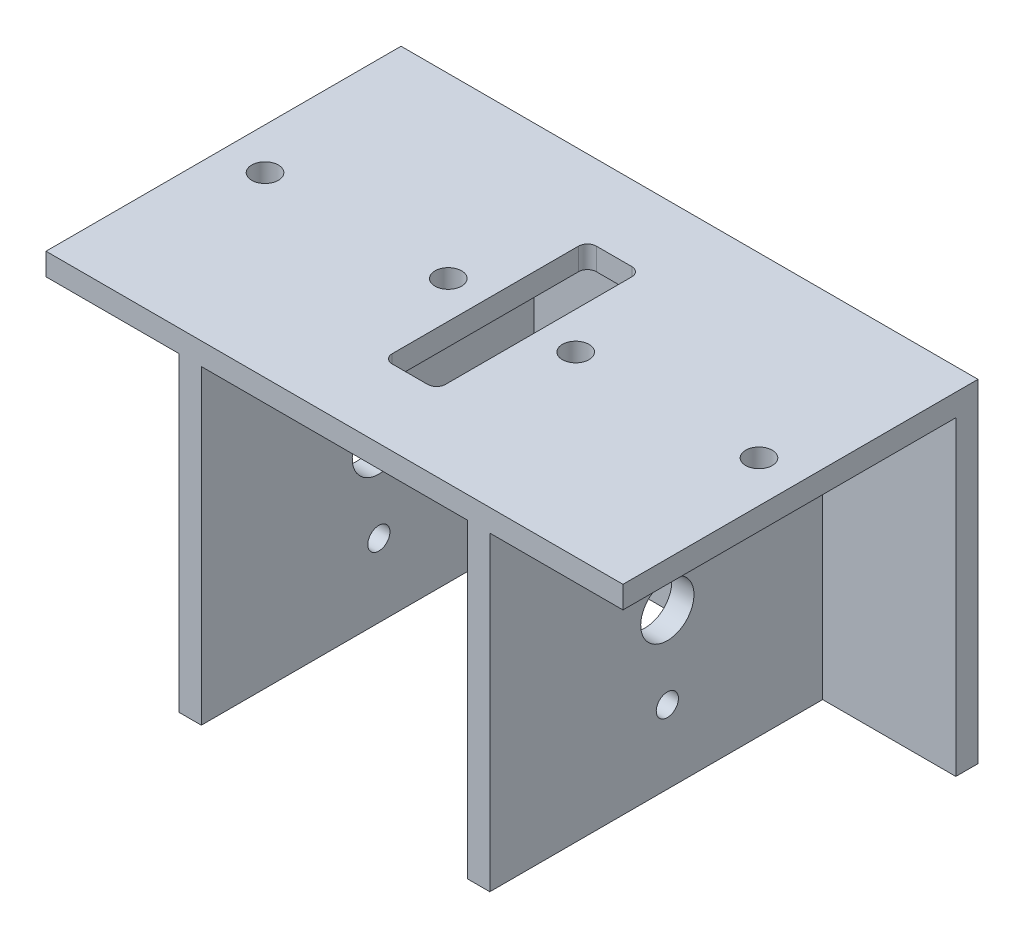
SolidWorks part; units mm, degrees
ref_plane "Front Plane" through (0, 0, 0) normal (0, 0, 1) x (1, 0, 0)
ref_plane "Top Plane" through (0, 0, 0) normal (0, 1, 0) x (1, 0, 0)
ref_plane "Right Plane" through (0, 0, 0) normal (1, 0, 0) x (0, 0, -1)
sketch "Sketch1" plane through (0, 0, 0) normal (0, 1, 0) x (1, 0, 0)
  line L0 (0, 18.2197) -> (0, -18.3609) construction
  line L1 (-19.3496, 0) -> (20.197, 0) construction
  line L2 (-35, 0) -> (-35, -10) construction
  line L3 (65, 40) -> (-65, 40)
  line L4 (-65, 40) -> (-65, -40)
  line L5 (65, -40) -> (-65, -40)
  line L6 (65, 40) -> (65, -40)
  line L7 (6, 23) -> (-6, 23)
  line L8 (-6, 23) -> (-6, -23)
  line L9 (6, -23) -> (-6, -23)
  line L10 (6, 23) -> (6, -23)
  circle A0 centre (-35, 0) radius 10 construction
  circle A1 centre (-14.35, 0) radius 3.4 construction
  circle A2 centre (-55.65, 0) radius 3.4 construction
  circle A3 centre (-14.35, 0) radius 3
  circle A4 centre (-55.65, 0) radius 3
  circle A5 centre (55.65, 0) radius 3
  circle A6 centre (55.65, 0) radius 3.4 construction
  circle A7 centre (35, 0) radius 10 construction
  circle A8 centre (14.35, 0) radius 3.4 construction
  circle A9 centre (14.35, 0) radius 3
  point P18 (-65, 0)
  point P20 (0, 40)
  point P21 (0, -40)
  point P33 (-6, 0)
  point P35 (0, -23)
  point P36 (0, 23)
  dimension "D1" = 20
  dimension "D3" = 6.8
  dimension "D4" = 41.3
  dimension "D5" = 6
  dimension "D2" = 70
  dimension "D6" = 130
  dimension "D7" = 80
  dimension "D8" = 12
  dimension "D9" = 46
extrude "Boss-Extrude1" add sketch "Sketch1" along normal blind 5
fillet "Fillet1" radius 2 4 edges at (6, 2.5, 23) (-6, 2.5, 23) (6, 2.5, -23) (-6, 2.5, -23)
sketch "Sketch2" plane through (0, 0, 0) normal (0, -1, 0) x (1, 0, 0)
  line L0 (-65, -40) -> (-65, -35)
  line L1 (-65, -40) -> (-65, 40) construction
  line L2 (-65, -35) -> (65, -35)
  line L3 (65, 40) -> (65, -40) construction
  line L4 (65, -35) -> (65, -40)
  line L5 (65, -40) -> (-65, -40)
  dimension "D1" = 5
extrude "Boss-Extrude2" add sketch "Sketch2" along normal blind 70
sketch "Sketch3" plane through (0, 0, -35) normal (0, 0, 1) x (1, 0, 0)
  line L0 (0, 0) -> (0, -70) construction
  line L1 (65, 0) -> (-65, 0) construction
  line L2 (65, -70) -> (-65, -70) construction
  line L3 (0, -35) -> (-65, -35) construction
  line L4 (-65, -70) -> (-65, 0) construction
  line L5 (0, -35) -> (65, -35) construction
  line L6 (65, -70) -> (65, 0) construction
  line L7 (-32.5, 0) -> (-32.5, -70) construction
  line L8 (32.5, 0) -> (32.5, -70) construction
  line L9 (-30, 0) -> (-35, 0)
  line L10 (-35, 0) -> (-35, -70)
  line L11 (-35, -70) -> (-30, -70)
  line L12 (-30, 0) -> (-30, -70)
  line L13 (30, 0) -> (30, -70)
  line L14 (35, -70) -> (30, -70)
  line L15 (35, 0) -> (35, -70)
  line L16 (30, 0) -> (35, 0)
  point P15 (-32.5, -35)
  point P18 (32.5, -35)
  dimension "D1" = 5
extrude "Boss-Extrude3" add sketch "Sketch3" along normal blind 75
sketch "Sketch4" plane through (-35, 0, 0) normal (-1, 0, 0) x (0, 0, 1)
  line L0 (0, 0) -> (0, -70) construction
  line L1 (40, -70) -> (-35, -70) construction
  line L2 (-35, -35) -> (40, -35) construction
  line L3 (-35, 0) -> (-35, -70) construction
  line L4 (40, 0) -> (40, -70) construction
  circle A0 centre (0, -35) radius 6
  circle A1 centre (0, -35) radius 18.5 construction
  circle A2 centre (0, -16.5) radius 2.5
  circle A3 centre (0, -53.5) radius 2.5
  dimension "D1" = 12
  dimension "D2" = 37
  dimension "5" = 5
extrude "Cut-Extrude1" cut sketch "Sketch4" against normal through all both and the other way through all
